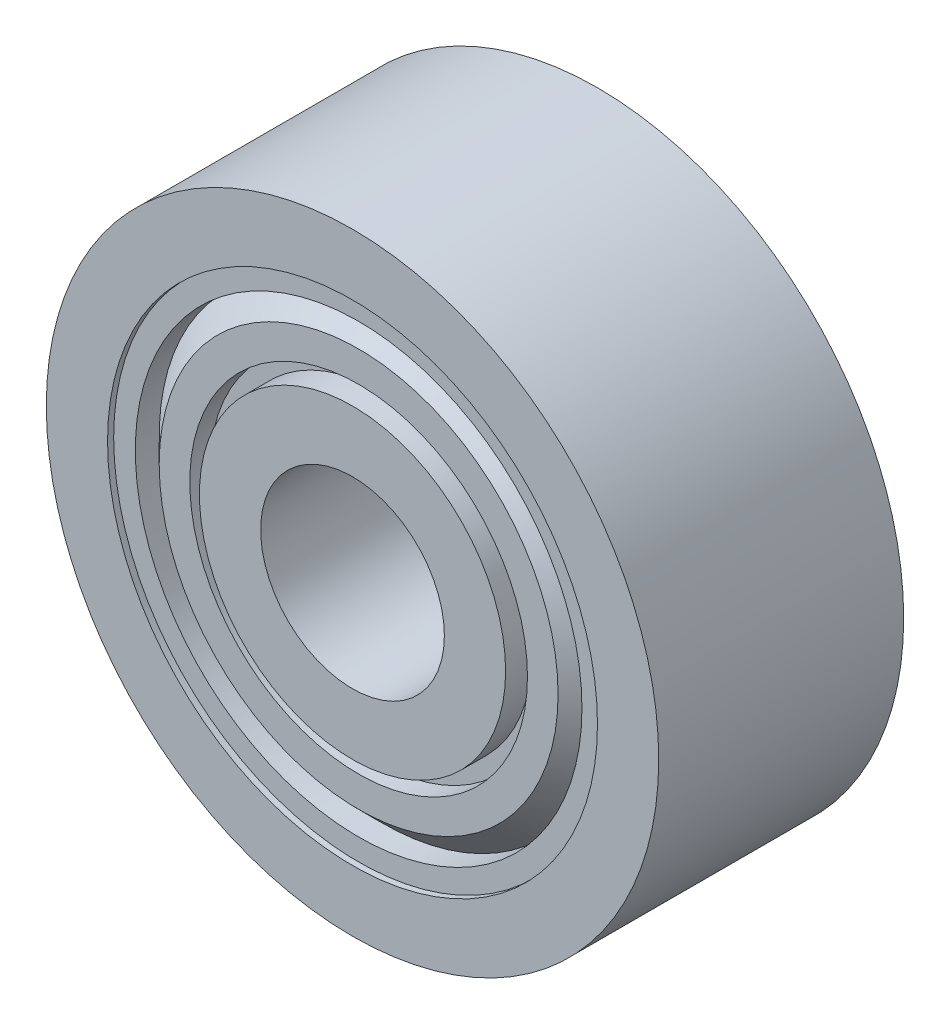
SolidWorks part; units mm, degrees
ref_plane "Plan de face" through (0, 0, 0) normal (0, 0, 1) x (1, 0, 0)
ref_plane "Plan de dessus" through (0, 0, 0) normal (0, 1, 0) x (1, 0, 0)
ref_plane "Plan de droite" through (0, 0, 0) normal (1, 0, 0) x (0, 0, -1)
sketch "Esquisse2" plane through (0, 0, 0) normal (1, 0, 0) x (0, 0, -1)
  line L0 (-4.422, 0) -> (6.828, 0) construction
  line L1 (0, 2.9906) -> (0, -3.004) construction
  line L2 (2, 1.5) -> (-2, 1.5)
  line L3 (-2, 1.5) -> (-2, 2.5)
  line L4 (-2, 2.5) -> (-1.5747, 2.5)
  line L5 (-1.5747, 2.5) -> (-1.5747, 2.7567)
  line L6 (-1.5747, 2.7567) -> (-1.9, 2.7567)
  line L7 (-1.9, 2.7567) -> (-1.9, 3.2567)
  line L8 (-1.9, 3.2567) -> (-1.5102, 3.6465)
  line L9 (-1.5102, 3.6465) -> (-1.9, 3.6465)
  line L10 (-1.9, 3.6465) -> (-1.9, 4)
  line L11 (-1.9, 4) -> (-2, 4)
  line L12 (-2, 4) -> (-2, 5)
  line L13 (-2, 5) -> (2, 5)
  line L14 (2, 4) -> (2, 5)
  line L15 (1.9, 4) -> (2, 4)
  line L16 (1.9, 3.6465) -> (1.9, 4)
  line L17 (1.5102, 3.6465) -> (1.9, 3.6465)
  line L18 (1.9, 3.2567) -> (1.5102, 3.6465)
  line L19 (1.9, 2.7567) -> (1.9, 3.2567)
  line L20 (1.5747, 2.7567) -> (1.9, 2.7567)
  line L21 (1.5747, 2.5) -> (1.5747, 2.7567)
  line L22 (2, 2.5) -> (1.5747, 2.5)
  line L23 (2, 1.5) -> (2, 2.5)
  point P1 (-2, 4.8629)
  point P19 (0, 5)
  point P29 (0, 1.5)
  dimension "D1" = 4
  dimension "D2" = 5
  dimension "D3" = 1.5
  dimension "D4" = 1
  dimension "D5" = 0.5
  dimension "D6" = 1
  dimension "D7" = 0.1
revolve "Révolution1" add sketch "Esquisse2" angle 360 about L0
